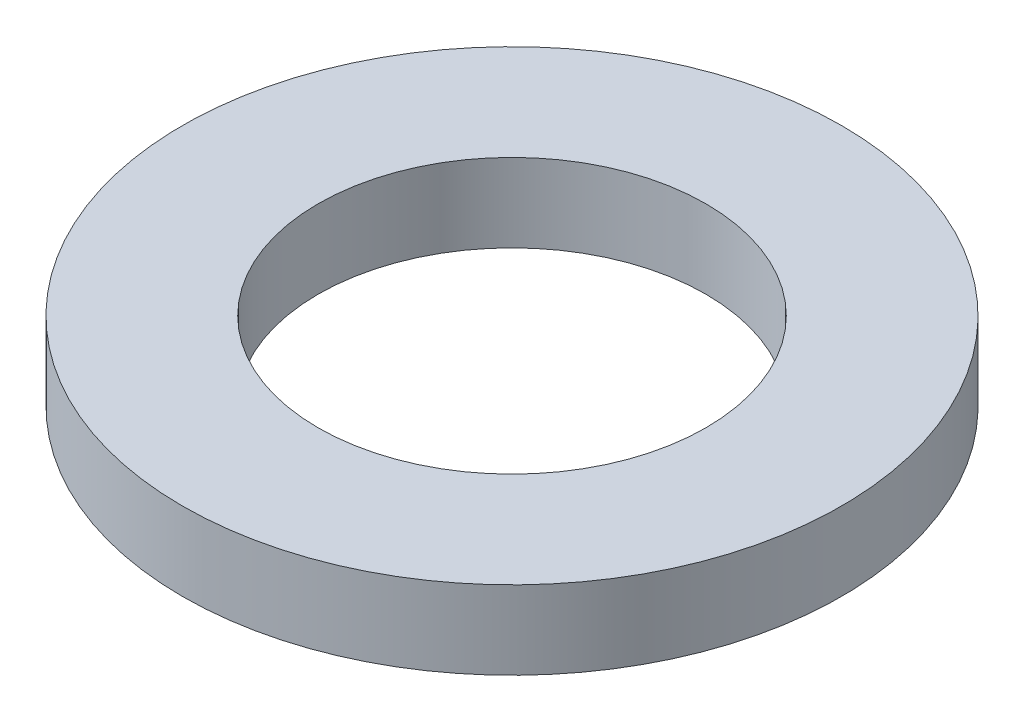
SolidWorks part; units mm, degrees
ref_plane "Front Plane" through (0, 0, 0) normal (0, 0, 1) x (1, 0, 0)
ref_plane "Top Plane" through (0, 0, 0) normal (0, 1, 0) x (1, 0, 0)
ref_plane "Right Plane" through (0, 0, 0) normal (1, 0, 0) x (0, 0, -1)
sketch "Sketch1" plane through (0, 0, 0) normal (0, 1, 0) x (1, 0, 0)
  circle A0 centre (0, 0) radius 11.1125
  dimension "OD" = 22.225
extrude "Boss-Extrude1" add sketch "Sketch1" along normal blind 2.6416
sketch "Sketch5" plane through (0, 2.6416, 0) normal (0, 1, 0) x (-1, 0, 0)
  circle A0 centre (0, 0) radius 6.5405
  dimension "ID" = 13.081
extrude "Cut-Extrude1" cut sketch "Sketch5" against normal through all
